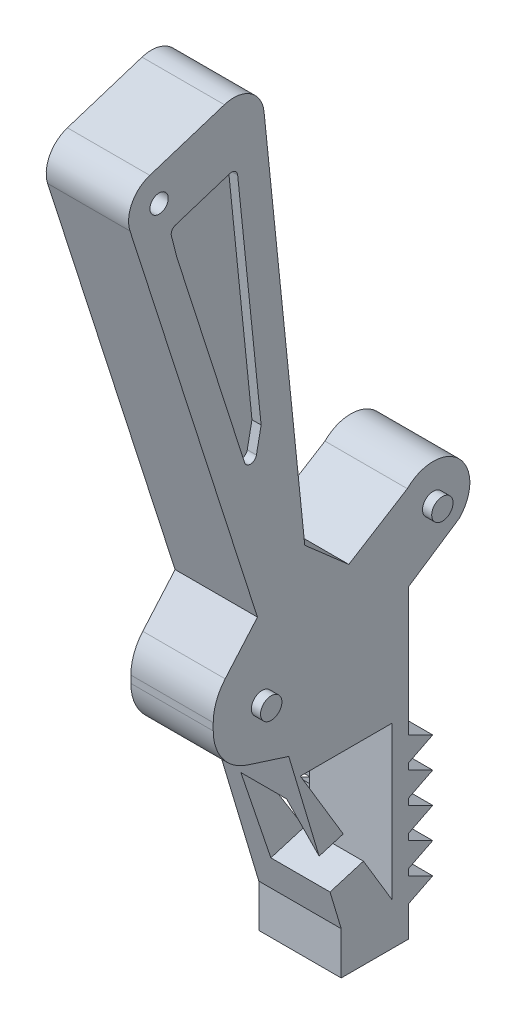
SolidWorks part; units mm, degrees
ref_plane "Front Plane" through (0, 0, 0) normal (0, 0, 1) x (1, 0, 0)
ref_plane "Top Plane" through (0, 0, 0) normal (0, 1, 0) x (1, 0, 0)
ref_plane "Right Plane" through (0, 0, 0) normal (1, 0, 0) x (0, 0, -1)
sketch "Sketch2" plane through (0, 0, 0) normal (1, 0, 0) x (0, 0, -1)
  line L0 (20.3295, 7.4102) -> (-2.0791, 77.4102)
  line L1 (-2.0791, 77.4102) -> (20.7783, 84.7274)
  line L2 (20.7783, 84.7274) -> (28.0815, 13.7274)
  line L4 (20.3295, 7.4102) -> (13.0815, -0.9555)
  line L5 (13.0815, -0.9555) -> (13.0815, -10.9555)
  line L6 (13.0815, -10.9555) -> (25.4602, -14.9262)
  line L7 (25.4602, -14.9262) -> (34.0526, -43.6694)
  line L8 (34.0526, -43.6694) -> (34.0526, -50.6694)
  line L9 (34.0526, -50.6694) -> (45.0526, -50.6694)
  line L10 (45.0526, -50.6694) -> (45.0526, -0.6694)
  line L11 (28.0815, 13.7274) -> (35.3029, 7.4102)
  line L13 (45.0526, -0.6694) -> (53.374, 4.8763)
  line L14 (35.3029, 7.4102) -> (44.8888, 13.3616)
  arc A0 (51.4141, 3.5702) -> (44.8888, 13.3616) centre (49.1314, 9.119) ccw
  dimension "D1" = 70
  dimension "D2" = 71
  dimension "D3" = 24
  dimension "D4" = 10
  dimension "D5" = 15
  dimension "D6" = 10
  dimension "D7" = 13
  dimension "D8" = 30
  dimension "D9" = 7
  dimension "D10" = 11
  dimension "D11" = 50
  dimension "D12" = 12
  dimension "D13" = 10
extrude "Boss-Extrude2" add sketch "Sketch2" along normal mid plane 13.5 contours L13 A0 L14 L11 L2 L1 L0 L4 L5 L6 L7 L8 L9 L10
sketch "Sketch4" plane through (6.75, 0, 0) normal (1, 0, 0) x (0, 0, -1)
  line L0 (42.3526, -43.6694) -> (42.3526, -18.6694)
  line L1 (42.3526, -18.6694) -> (27.3526, -18.6694)
  line L2 (27.3526, -18.6694) -> (42.3526, -43.6694)
  line L3 (34.0526, -43.6694) -> (42.6611, -43.6694) construction
  line L4 (45.0526, -50.6694) -> (45.0526, -0.6694) construction
  dimension "D1" = 15
  dimension "D2" = 25
  dimension "D3" = 0
  dimension "D4" = 2.7
extrude "Cut-Extrude1" cut sketch "Sketch4" against normal through all
sketch "Sketch5" plane through (6.75, 0, 0) normal (1, 0, 0) x (0, 0, -1)
  line L0 (45.0526, -41.6694) -> (45.0526, -45.6694)
  line L1 (45.0526, -50.6694) -> (45.0526, -0.6694) construction
  line L2 (45.0526, -45.6694) -> (49.0526, -43.6694)
  line L3 (49.0526, -43.6694) -> (45.0526, -41.6694)
  line L5 (49.0526, -43.6694) -> (45.0526, -43.6694)
  line M24 (45.0526, -50.6694) -> (45.0526, -0.6694)
  dimension "D1" = 4
  dimension "D2" = 2
  dimension "D3" = 4
  dimension "D4" = 5
extrude "Boss-Extrude3" add sketch "Sketch5" against normal blind 18 contours L5 L3 L0 | L2 L5 M24
pattern_linear "LPattern1" count 5 spacing 5 along (0, 1, 0) of "Boss-Extrude3"
fillet "Fillet1" radius 8 2 edges at (0, -10.9555, -13.0815) (0, -0.9555, -13.0815)
fillet "Fillet2" radius 5 2 edges at (0, 84.7274, -20.7783) (0, 77.4102, 2.0791)
sketch "Sketch6" plane through (6.75, 0, 0) normal (1, 0, 0) x (0, 0, -1)
  circle A0 centre (4.2073, 74.1727) radius 1.5
  dimension "D1" = 3
extrude "Cut-Extrude2" cut sketch "Sketch6" against normal through all
sketch "Sketch8" plane through (0, 5.7622, -19.2757) normal (0, -0.2864, 0.9581) x (1, 0, 0)
  line L0 (-3.75, -30.8345) -> (3.75, -30.8345)
  line L10 (12.1257, -21.593) -> (0, -51.593) construction
  line L11 (6.75, -21.593) -> (-6.75, -21.593) construction
  line L12 (6.75, -51.593) -> (-6.75, -51.593) construction
  line L13 (-6.75, -21.593) -> (-6.75, -51.593) construction
  line L14 (6.75, -21.593) -> (6.75, -51.593) construction
  line L15 (-2.9452, -45.202) -> (9.0548, -45.202)
  line L16 (-3.75, -30.8345) -> (-2.9452, -45.202)
  line L17 (3.75, -30.8345) -> (9.0548, -45.202)
  dimension "D1" = 3
  dimension "D2" = 3
  dimension "D3" = 12
  dimension "D4" = 6
extrude "Cut-Extrude4" cut sketch "Sketch8" against normal blind 8
sketch "Sketch9" plane through (6.75, 0, 0) normal (1, 0, 0) x (0, 0, -1)
  circle A0 centre (49.1314, 9.119) radius 1.75
  dimension "D1" = 3.5
extrude "Boss-Extrude4" add sketch "Sketch9" along normal blind 1.5
sketch "Sketch10" plane through (6.75, 0, 0) normal (1, 0, 0) x (0, 0, -1)
  circle A0 centre (21.0815, -5.1202) radius 1.75
  dimension "D1" = 3.5
extrude "Boss-Extrude5" add sketch "Sketch10" along normal blind 1.5
sketch "Sketch11" plane through (6.75, 0, 0) normal (1, 0, 0) x (0, 0, -1)
  line L0 (20.3295, 7.4102) -> (-0.5547, 72.6483) construction
  line L1 (6.8869, 69.7805) -> (16.0352, 72.7091)
  line L2 (2.6829, 78.9346) -> (14.9105, 82.849) construction
  line L3 (7.1152, 65.089) -> (6.2229, 68.5805)
  line L4 (17.0757, 71.8582) -> (16.8093, 74.4473)
  line L5 (16.0352, 72.7091) -> (15.7842, 72.6288)
  line L6 (20.1553, 30.5007) -> (20.9313, 34.3743)
  line L28 (17.0838, 71.7787) -> (20.9313, 34.3743)
  line L29 (21.4087, 78.5986) -> (28.0815, 13.7274) construction
  line L30 (7.1152, 65.089) -> (18.2224, 30.3922)
  arc A0 (17.0838, 71.7787) -> (15.7842, 72.6288) centre (16.0891, 71.6764) ccw
  arc A1 (6.2229, 68.5805) -> (6.8869, 69.7805) centre (7.1917, 68.8281) cw
  arc A2 (18.2224, 30.3922) -> (20.1553, 30.5007) centre (19.1748, 30.6971) ccw
  dimension "D1" = 1
  dimension "D2" = 1
  dimension "D3" = 5
  dimension "D4" = 5
  dimension "D5" = 10
extrude "Cut-Extrude6" cut sketch "Sketch11" against normal blind 1.5 and the other way through all contours L30 A2 L6 L28 A0 L1 A1 L3
ref_plane "Plane1" through (0, 0, 0) normal (1, 0, 0) x (0, 0, -1)
mirror "Mirror1" about plane through (0, 0, 0) normal (1, 0, 0) of "Boss-Extrude4", "Boss-Extrude5", "Cut-Extrude6"
